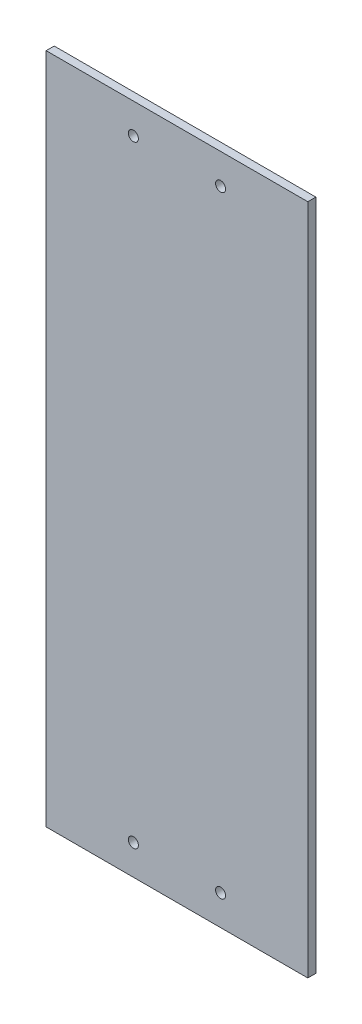
SolidWorks part; units mm, degrees
ref_plane "Alzado" through (0, 0, 0) normal (0, 0, 1) x (1, 0, 0)
ref_plane "Planta" through (0, 0, 0) normal (0, 1, 0) x (1, 0, 0)
ref_plane "Vista lateral" through (0, 0, 0) normal (1, 0, 0) x (0, 0, -1)
sketch "Croquis1" plane through (0, 0, 0) normal (0, 0, 1) x (1, 0, 0)
  line L0 (53.6763, 179.8761) -> (-76.3237, 179.8761)
  line L1 (53.6763, 179.8761) -> (53.6763, -154.1239)
  line L2 (53.6763, -154.1239) -> (-76.3237, -154.1239)
  line L3 (-76.3237, 179.8761) -> (-76.3237, -154.1239)
  circle A0 centre (10.343, 164.8761) radius 2.5
  circle A1 centre (-32.9904, 164.8761) radius 2.5
  circle A2 centre (10.343, -139.1239) radius 2.5
  circle A3 centre (-32.9904, -139.1239) radius 2.5
extrude "Saliente-Extruir1" add sketch "Croquis1" along normal blind 4
